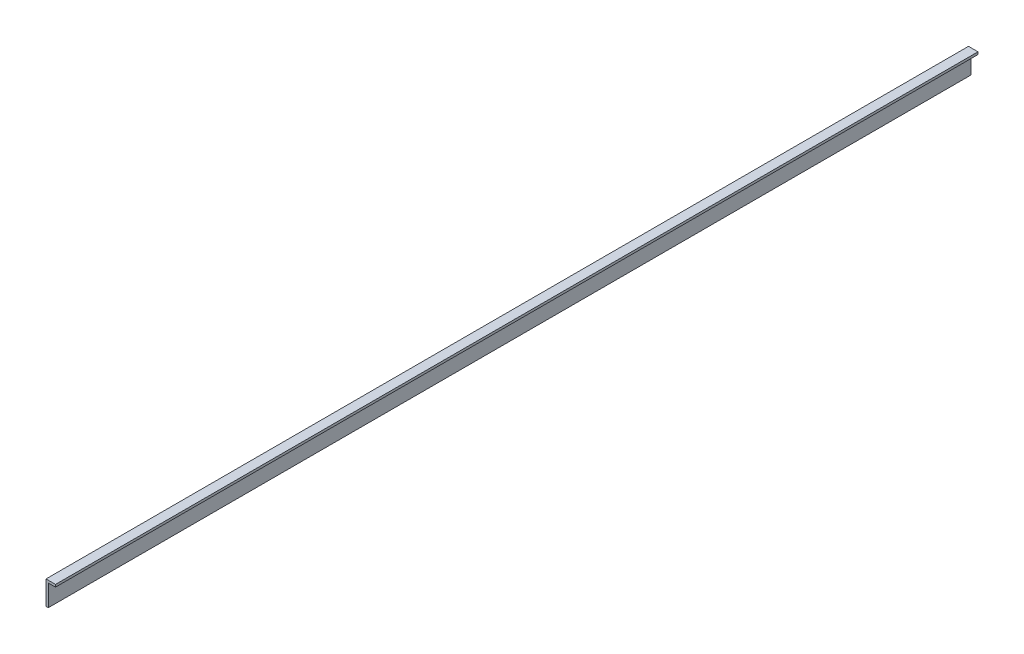
SolidWorks part; units mm, degrees
ref_plane "Front Plane" through (0, 0, 0) normal (0, 0, 1) x (1, 0, 0)
ref_plane "Top Plane" through (0, 0, 0) normal (0, 1, 0) x (1, 0, 0)
ref_plane "Right Plane" through (0, 0, 0) normal (1, 0, 0) x (0, 0, -1)
other "Configuration Table"
sketch "Sketch1" plane through (0, 0, 0) normal (0, 0, 1) x (1, 0, 0)
  line L0 (-54, 0) -> (-56, 0)
  line L1 (-56, 0) -> (-56, 20)
  line L2 (-56, 20) -> (-48, 20)
  line L3 (-48, 20) -> (-48, 18)
  line L4 (-48, 18) -> (-54, 18)
  line L5 (-54, 18) -> (-54, 0)
extrude "LRAF_sol_20x8x2_1" add sketch "Sketch1" against normal blind 777.5 from offset 20 separate body
